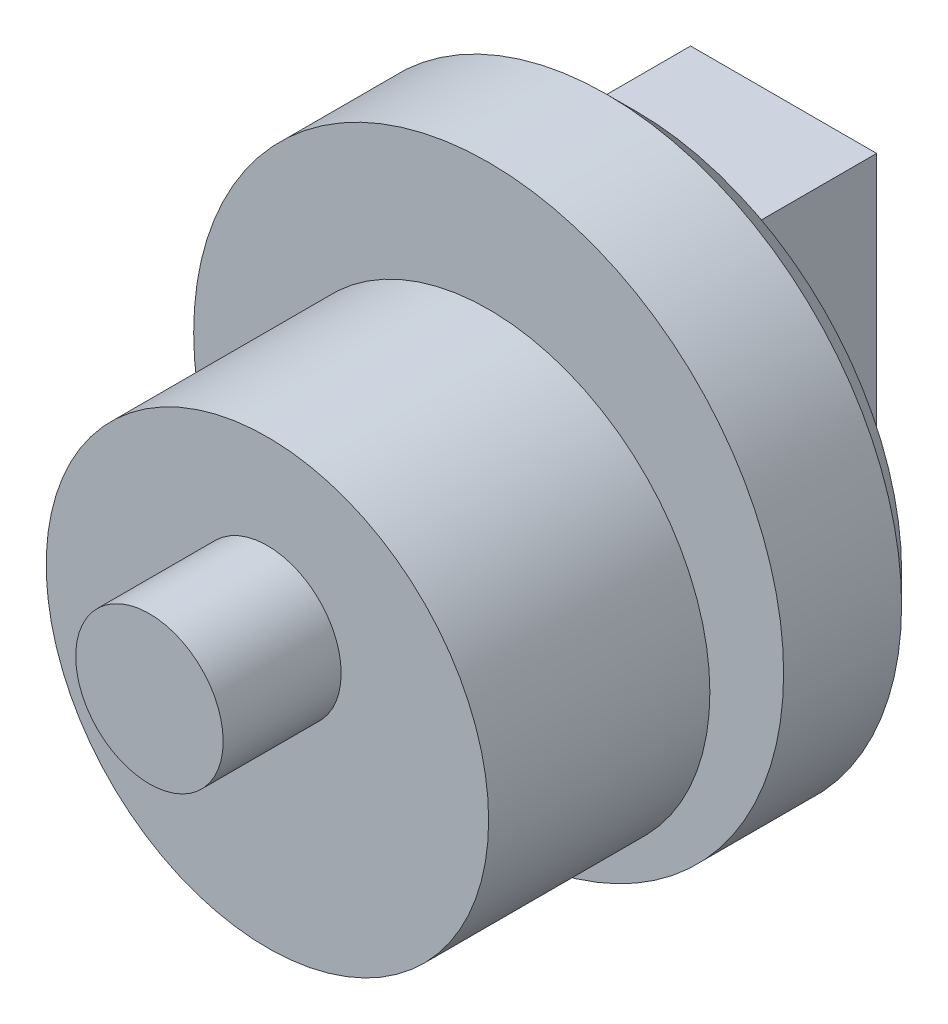
SolidWorks part; units mm, degrees
ref_plane "Front Plane" through (0, 0, 0) normal (0, 0, 1) x (1, 0, 0)
ref_plane "Top Plane" through (0, 0, 0) normal (0, 1, 0) x (1, 0, 0)
ref_plane "Right Plane" through (0, 0, 0) normal (1, 0, 0) x (0, 0, -1)
sketch "Sketch1" plane through (0, 0, 0) normal (0, 0, 1) x (1, 0, 0)
  circle A0 centre (0, 0) radius 10
  dimension "D1" = 20
extrude "Boss-Extrude1" add sketch "Sketch1" along normal blind 5
sketch "Sketch2" plane through (0, 0, 5) normal (0, 0, 1) x (1, 0, 0)
  circle A0 centre (0, -1.812) radius 7.5
  dimension "D1" = 15
  dimension "D2" = 1.812
extrude "Boss-Extrude2" add sketch "Sketch2" along normal blind 7.5
sketch "Sketch3" plane through (0, 0, 12.5) normal (0, 0, 1) x (1, 0, 0)
  circle A0 centre (0, 0) radius 2.5
  dimension "D1" = 5
extrude "Boss-Extrude3" add sketch "Sketch3" along normal blind 4
sketch "Sketch4" plane through (0, 0, 0) normal (0, 0, -1) x (-1, 0, 0)
  line L1 (-3.1533, 6.8398) -> (3.1533, 6.8398)
  line L2 (-3.1533, 6.8398) -> (-3.1533, -6.8398)
  line L3 (-3.1533, -6.8398) -> (3.1533, -6.8398)
  line L4 (3.1533, 6.8398) -> (3.1533, -6.8398)
  line L5 (-3.1533, 6.8398) -> (3.1533, -6.8398) construction
  line L6 (-3.1533, -6.8398) -> (3.1533, 6.8398) construction
  point P0 (0, 0)
extrude "Boss-Extrude4" add sketch "Sketch4" along normal blind 5
chamfer "Chamfer2" distance 1 angle 45 1 edges at (10, 0, 0)
